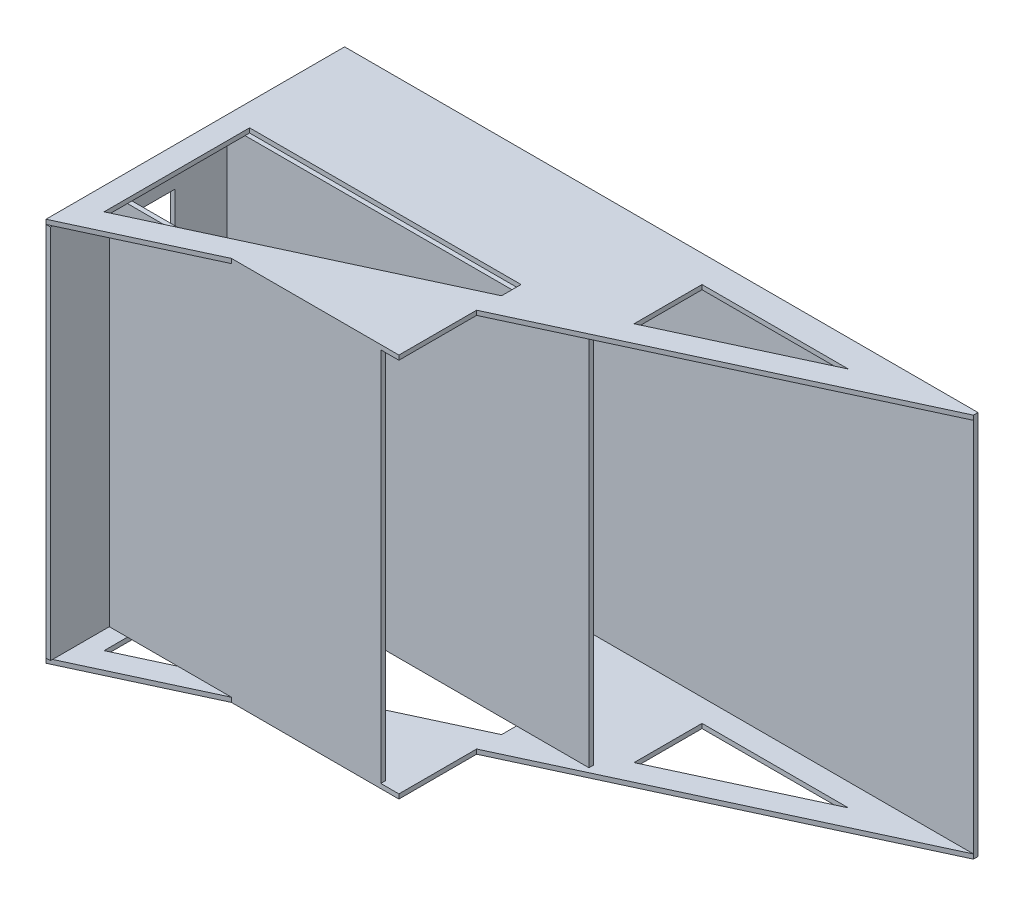
SolidWorks part; units mm, degrees
ref_plane "Front Plane" through (0, 0, 0) normal (0, 0, 1) x (1, 0, 0)
ref_plane "Top Plane" through (0, 0, 0) normal (0, 1, 0) x (1, 0, 0)
ref_plane "Right Plane" through (0, 0, 0) normal (1, 0, 0) x (0, 0, -1)
sketch "Sketch1" plane through (0, 0, 0) normal (0, 1, 0) x (1, 0, 0)
  line L1 (0, 0) -> (215.9, 0)
  line L2 (0, 0) -> (0, 355.6)
  line L3 (0, 355.6) -> (215.9, 355.6)
  line L4 (215.9, 0) -> (215.9, 355.6)
  dimension "D1" = 355.6
  dimension "D2" = 215.9
extrude "Boss-Extrude1" add sketch "Sketch1" along normal blind 2.54
sketch "Sketch2" plane through (215.9, 0, 0) normal (1, 0, 0) x (0, 0, -1)
  line L0 (355.6, 2.54) -> (355.6, 167.64)
  line L1 (355.6, 167.64) -> (0, 2.54)
  line L2 (0, 2.54) -> (355.6, 2.54)
  line L3 (139.7, 53.3986) -> (139.7, 15.24)
  line L4 (139.7, 15.24) -> (57.5121, 15.24)
  line L5 (57.5121, 15.24) -> (139.7, 53.3986)
  line L6 (342.9, 147.7415) -> (342.9, 66.04)
  line L7 (342.9, 66.04) -> (190.5, 66.04)
  line L8 (190.5, 76.9844) -> (342.9, 147.7415)
  line L9 (190.5, 66.04) -> (190.5, 76.9844)
  line L10 (355.6, 134.62) -> (190.5, 134.62)
  line L11 (190.5, 134.62) -> (190.5, 90.9864)
  line L12 (190.5, 90.9864) -> (284.48, 134.62)
  dimension "D1" = 165.1
  dimension "D2" = 12.7
  dimension "D3" = 12.7
  dimension "D4" = 12.7
  dimension "D5" = 12.7
  dimension "D6" = 63.5
  dimension "D7" = 50.8
  dimension "D8" = 215.9
  dimension "D9" = 33.02
  dimension "D10" = 165.1
extrude "Boss-Extrude2" add sketch "Sketch2" against normal blind 2.54 contours L2 L0 L1
sketch "Sketch3" plane through (215.9, 0, 0) normal (1, 0, 0) x (0, 0, -1)
  line L0 (139.7, 15.24) -> (57.5121, 15.24) construction
  line L1 (139.7, 53.3986) -> (139.7, 15.24) construction
  line L2 (57.5121, 15.24) -> (139.7, 53.3986) construction
  line L3 (190.5, 66.04) -> (190.5, 76.9844) construction
  line L4 (342.9, 66.04) -> (190.5, 66.04) construction
  line L5 (342.9, 147.7415) -> (342.9, 66.04) construction
  line L6 (190.5, 76.9844) -> (342.9, 147.7415) construction
  line L7 (139.7, 15.24) -> (57.5121, 15.24)
  line L8 (139.7, 53.3986) -> (139.7, 15.24)
  line L9 (57.5121, 15.24) -> (139.7, 53.3986)
  line L10 (190.5, 66.04) -> (190.5, 76.9844)
  line L11 (342.9, 66.04) -> (190.5, 66.04)
  line L12 (342.9, 147.7415) -> (342.9, 66.04)
  line L13 (190.5, 76.9844) -> (342.9, 147.7415)
extrude "Cut-Extrude4" cut sketch "Sketch3" against normal blind 2.54
sketch "Sketch5" plane through (0, 0, 0) normal (-1, 0, 0) x (0, 0, 1)
  line L3 (0, 2.54) -> (-355.6, 167.64)
  line L4 (-355.6, 167.64) -> (-355.6, 2.54)
  line L5 (-355.6, 2.54) -> (0, 2.54)
  line L6 (0, 2.54) -> (-355.6, 167.64)
  line L7 (-355.6, 167.64) -> (-355.6, 2.54)
  line L8 (-355.6, 2.54) -> (0, 2.54)
  dimension "D1" = 0
extrude "Boss-Extrude3" add sketch "Sketch5" against normal blind 2.54
sketch "Sketch6" plane through (0, 0, 0) normal (-1, 0, 0) x (0, 0, 1)
  line L0 (-139.7, 15.24) -> (-57.5121, 15.24) construction
  line L1 (-139.7, 53.3986) -> (-139.7, 15.24) construction
  line L2 (-57.5121, 15.24) -> (-139.7, 53.3986) construction
  line L3 (-342.9, 66.04) -> (-190.5, 66.04) construction
  line L4 (-342.9, 147.7415) -> (-342.9, 66.04) construction
  line L5 (-190.5, 66.04) -> (-190.5, 76.9844) construction
  line L6 (-190.5, 76.9844) -> (-342.9, 147.7415) construction
  line L7 (-139.7, 15.24) -> (-57.5121, 15.24)
  line L8 (-139.7, 53.3986) -> (-139.7, 15.24)
  line L9 (-57.5121, 15.24) -> (-139.7, 53.3986)
  line L10 (-342.9, 66.04) -> (-190.5, 66.04)
  line L11 (-342.9, 147.7415) -> (-342.9, 66.04)
  line L12 (-190.5, 66.04) -> (-190.5, 76.9844)
  line L13 (-190.5, 76.9844) -> (-342.9, 147.7415)
extrude "Cut-Extrude5" cut sketch "Sketch6" against normal blind 2.54
sketch "Sketch7" plane through (0, 0, -355.6) normal (0, 0, -1) x (-1, 0, 0)
  line L0 (-213.36, 167.64) -> (-2.54, 2.54) construction
  line L1 (-213.36, 2.54) -> (-2.54, 2.54)
  line L2 (-213.36, 2.54) -> (-213.36, 167.64)
  line L3 (-213.36, 167.64) -> (-2.54, 167.64)
  line L4 (-2.54, 2.54) -> (-2.54, 167.64)
  line L5 (-196.85, 15.24) -> (-19.05, 15.24)
  line L6 (-196.85, 15.24) -> (-196.85, 46.99)
  line L7 (-196.85, 46.99) -> (-19.05, 46.99)
  line L8 (-19.05, 15.24) -> (-19.05, 46.99)
  line L9 (-196.85, 97.79) -> (-19.05, 97.79)
  line L10 (-196.85, 97.79) -> (-196.85, 129.54)
  line L11 (-196.85, 129.54) -> (-19.05, 129.54)
  line L12 (-19.05, 97.79) -> (-19.05, 129.54)
  point P14 (-107.95, 129.54)
  point P15 (-107.95, 85.09)
  point P16 (-107.95, 46.99)
  dimension "D1" = 177.8
  dimension "D2" = 31.75
  dimension "D3" = 12.7
  dimension "D4" = 50.8
extrude "Boss-Extrude4" add sketch "Sketch7" against normal blind 2.54
sketch "Sketch8" plane through (0, 0, -353.06) normal (0, 0, 1) x (1, 0, 0)
  line L0 (2.54, 2.54) -> (2.54, 166.4607) construction
  line L1 (2.54, 68.58) -> (213.36, 68.58)
  line L2 (2.54, 68.58) -> (2.54, 66.04)
  line L3 (2.54, 66.04) -> (213.36, 66.04)
  line L4 (213.36, 68.58) -> (213.36, 66.04)
  line L5 (213.36, 166.4607) -> (213.36, 2.54) construction
  line L6 (213.36, 2.54) -> (2.54, 2.54) construction
  dimension "D1" = 2.54
  dimension "D2" = 63.5
extrude "Boss-Extrude6" add sketch "Sketch8" along normal blind 203.2 separate body
sketch "Sketch9" plane through (0, 0, -353.06) normal (0, 0, 1) x (1, 0, 0)
  line L0 (2.54, 2.54) -> (2.54, 166.4607) construction
  line L1 (2.54, 134.62) -> (213.36, 134.62)
  line L2 (2.54, 134.62) -> (2.54, 132.08)
  line L3 (2.54, 132.08) -> (213.36, 132.08)
  line L4 (213.36, 134.62) -> (213.36, 132.08)
  line L5 (213.36, 166.4607) -> (213.36, 2.54) construction
  line L6 (213.36, 68.58) -> (2.54, 68.58) construction
  dimension "D1" = 63.5
  dimension "D2" = 2.54
extrude "Boss-Extrude7" add sketch "Sketch9" along normal blind 152.4
sketch "Sketch10" plane through (215.9, 0, 0) normal (1, 0, 0) x (0, 0, -1)
  line L0 (190.5, 134.62) -> (190.5, 90.9864) construction
  line L1 (355.6, 134.62) -> (190.5, 134.62) construction
  line L2 (190.5, 134.62) -> (190.5, 90.9864)
  line L3 (355.6, 134.62) -> (190.5, 134.62)
  line L4 (190.5, 90.9864) -> (284.48, 134.62)
  line M10 (355.6, 167.64) -> (0, 2.54)
extrude "Boss-Extrude8" add sketch "Sketch10" against normal up to vertex contours L3 L2 M10
sketch "Sketch11" plane through (0, 0, 0) normal (-1, 0, 0) x (0, 0, 1)
  line L0 (-355.6, 134.62) -> (-190.5, 134.62) construction
  line L1 (-190.5, 134.62) -> (-190.5, 90.9864) construction
  line L2 (-355.6, 134.62) -> (-190.5, 134.62)
  line L3 (-190.5, 134.62) -> (-190.5, 90.9864)
  line L4 (-284.48, 134.62) -> (-190.5, 90.9864)
  line M10 (0, 2.54) -> (-355.6, 167.64)
extrude "Boss-Extrude9" add sketch "Sketch11" against normal up to vertex contours L3 L2 M10
move or copy body "Body-Move/Copy1" bodies to move or copy 111 108 copy no translate (-107.95, 0, 0)
move or copy body "Body-Move/Copy2" bodies to move or copy 113 112 copy no rotation origin (46.355, 121.92, -168.275) rotation axis (0.5774, 0.5774, 0.5774) rotation angle 120
move or copy body "Body-Move/Copy3" bodies to move or copy 115 114 copy no translate (0, -75.692, 0)
equation "\"D3@Sketch2\"=\"D2@Sketch2\""
equation "\"D4@Sketch2\"=\"D2@Sketch2\""
equation "\"D5@Sketch2\"=\"D2@Sketch2\""
